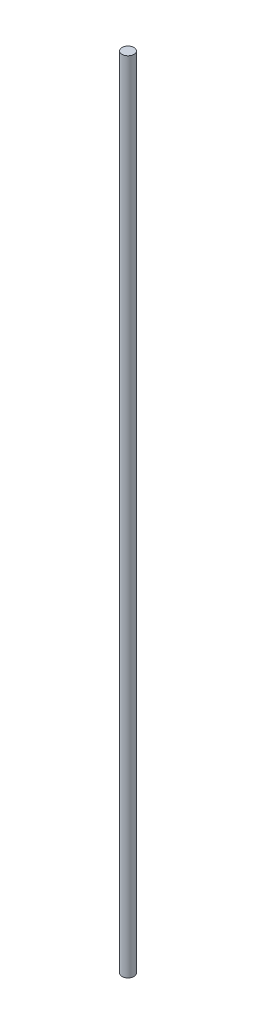
SolidWorks part; units mm, degrees
ref_plane "Alzado" through (0, 0, 0) normal (0, 0, 1) x (1, 0, 0)
ref_plane "Planta" through (0, 0, 0) normal (0, 1, 0) x (1, 0, 0)
ref_plane "Vista lateral" through (0, 0, 0) normal (1, 0, 0) x (0, 0, -1)
sketch "Croquis1" plane through (0, 0, 0) normal (0, 1, 0) x (1, 0, 0)
  circle A0 centre (0, 0) radius 7.5
  dimension "D1" = 15
extrude "Extruir1" add sketch "Croquis1" along normal blind 1000
